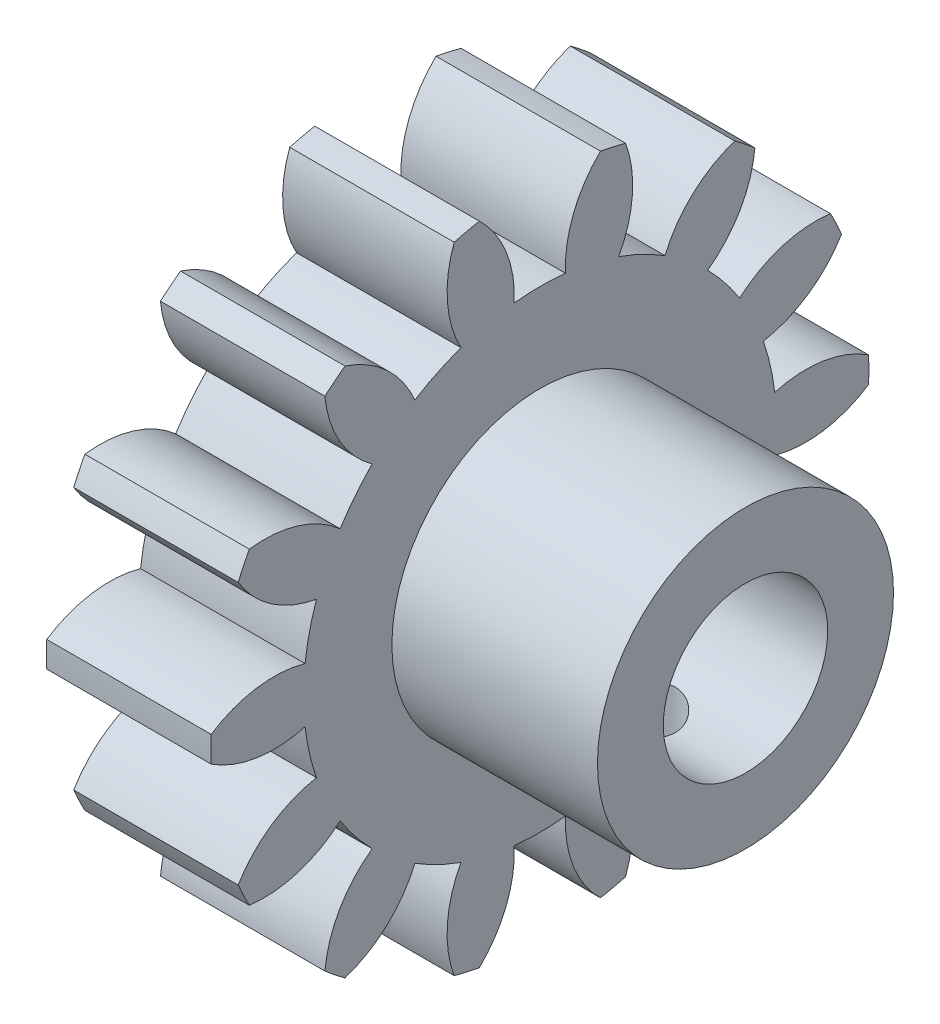
SolidWorks part; units mm, degrees
ref_plane "Plane1" through (0, 0, 0) normal (0, 0, 1) x (1, 0, 0)
ref_plane "Plane2" through (0, 0, 0) normal (0, 1, 0) x (1, 0, 0)
ref_plane "Plane3" through (0, 0, 0) normal (1, 0, 0) x (0, 0, -1)
other "Configuration Table"
sketch "HoldingSke" plane through (0, 0, 0) normal (0, 1, 0) x (1, 0, 0)
  line L0 (0, 0) -> (0.3881, -0.0968)
  line L1 (-15, 0) -> (100, 0) construction
  line L2 (0, 0) -> (-2.1039, 2.3779)
  line L3 (0, 0) -> (-11.863, 4.5341)
  line L4 (0, 0) -> (8.3795, 2.0892)
  line L5 (0, 0) -> (-46.8476, -17.4728)
  line L6 (0, 0) -> (-8.2896, -5.593)
  line L7 (-2.1039, 2.3779) -> (8.6586, 51.2059)
  line L8 (-76.2, 54.61) -> (-74.4, 54.61)
  line L9 (-67.7845, 28.3722) -> (-49.3413, 33.142)
  line L10 (-76.2, 71.12) -> (104.1128, 71.12)
  line L11 (0, 0) -> (-10, 0)
  line L12 (-76.2, 101.6) -> (-76.113, 101.6)
  line L13 (24.9733, 27.94) -> (52.9518, 28.4284)
  line L14 (24.9733, 27.94) -> (24.9743, 27.94)
  line L15 (24.9733, 27.94) -> (100.4006, 29.5858)
  line L16 (-63.627, -2.5) -> (-12.827, -2.5)
  circle A0 centre (0, 0) radius 5
  circle A1 centre (0, 0) radius 14.374
  circle A2 centre (0, 0) radius 37.5
  circle A3 centre (0, 0) radius 5
  dimension "MHD" = 28.748
  dimension "Hub_dia" = 75
  dimension "Bore" = 10
  dimension "MBD" = 10
  dimension "Num_teeth" = 14
  dimension "Pitch" = 0.4
  dimension "Overall_len" = 50
  dimension "Show_teeth" = 14
  dimension "Thickness" = 10
  dimension "OAL" = 50.0001
  dimension "T_dim" = 1.8
  dimension "Ap" = 14.5
  dimension "H" = 19.05
  dimension "Pitch_radius" = 180.3128
  dimension "Width" = 10
  dimension "Backlash" = 0.087
  dimension "Addendum_fac" = 1
  dimension "Dedendum_fac" = 1.25
  dimension "Clearance_fac" = 0.25
  dimension "Dedendum_add" = 0.001
  dimension "Module" = 2.5
sketch "BasProSke" plane through (0, 0, 0) normal (0, 1, 0) x (1, 0, 0)
  line L0 (-10, 0) -> (60, 0) construction
  line L1 (0, 0) -> (0, 20)
  line L2 (0, 0) -> (10, 0)
  line L3 (10, 0) -> (10, 20)
  line L4 (10, 20) -> (0, 20)
  dimension "Thickness" = 10
  dimension "Diameter" = 40
revolve "Base-Revolve" add sketch "BasProSke" angle 360 about L0
sketch "TooCutSke" plane through (0, 0, 0) normal (1, 0, 0) x (0, 0, -1)
  line L1 (0, 0) -> (0, 107) construction
  line L2 (0, 0) -> (-2.1115, 17.3722) construction
  line L3 (0, 0) -> (-7.7466, 33.9401) construction
  line L4 (-2.1115, 17.3722) -> (-3.8733, 16.97) construction
  arc A0 (1.5587, 14.2892) -> (-1.5587, 14.2892) centre (0, 0) ccw
  arc A1 (3.7061, 19.6795) -> (-3.7061, 19.6795) centre (0, 0) ccw
  circle A2 centre (0, 0) radius 17.5 construction
  circle A3 centre (0, 0) radius 16.9426 construction
  arc A4 (-1.5587, 14.2892) -> (-3.7061, 19.6795) centre (-8.5506, 14.6266) ccw
  arc A5 (3.7061, 19.6795) -> (1.5587, 14.2892) centre (8.5506, 14.6266) ccw
  dimension "Root_dia" = 28.748
  dimension "Overcut_dia" = 40.0508
  dimension "Pitch_dia" = 35
  dimension "Base_dia" = 33.8852
  dimension "Flank_rad" = 7
  dimension "Half_ang" = 12.857
  dimension "Half_CT" = 1.8071
extrude "ToothCut" cut sketch "TooCutSke" along normal through all
fillet "Breaks" [suppressed] radius 0.05
fillet "RootFillets" [suppressed] radius 0.626
pattern_circular "TeethCuts" count 14 every 25.714 about axis through (-10, 0, 0) along (1, 0, 0) of "ToothCut", "RootFillets", "Breaks"
sketch "HubNeaOneSke" plane through (0, 0, 0) normal (-1, 0, 0) x (0, 0, 1)
  circle A0 centre (0, 0) radius 14.374
  dimension "Diameter" = 28.748
extrude "HubNearOne" [suppressed] add sketch "HubNeaOneSke" along normal blind 40.0001
sketch "HubNeaBotSke" plane through (0, 0, 0) normal (-1, 0, 0) x (0, 0, 1)
  circle A0 centre (0, 0) radius 14.374
  dimension "Diameter" = 28.748
extrude "HubNearBoth" [suppressed] add sketch "HubNeaBotSke" along normal blind 20
ref_plane "FarPln" through (10, 0, 0) normal (1, 0, 0) x (0, 0, -1)
sketch "HubFarSke" plane through (10, 0, 0) normal (1, 0, 0) x (0, 0, -1)
  circle A0 centre (0, 0) radius 14.374
  dimension "Diameter" = 28.748
extrude "HubFar" [suppressed] add sketch "HubFarSke" along normal blind 20
sketch "BorSke" plane through (0, 0, 0) normal (1, 0, 0) x (0, 0, -1)
  circle A0 centre (0, 0) radius 5
  dimension "Diameter" = 10
extrude "Bore" cut sketch "BorSke" along normal mid plane 100.0001
sketch "KeySke" plane through (0, 0, 0) normal (1, 0, 0) x (0, 0, -1)
  line L0 (-2, 0) -> (-2, 6.8)
  line L1 (-2, 6.8) -> (2, 6.8)
  line L2 (2, 6.8) -> (2, 0)
  line L3 (0, 0) -> (0, 34) construction
  line L4 (-2, 0) -> (2, 0)
  dimension "Offset" = 6.8
  dimension "Width" = 4
extrude "Keyway" [suppressed] cut sketch "KeySke" along normal mid plane 100.0001
pattern_circular "Keyway2" [suppressed] count 2 every 90 about axis through (-10, 0, 0) along (1, 0, 0)
sketch "Esquisse1" plane through (10, 0, 0) normal (1, 0, 0) x (0, 0, -1)
  circle A0 centre (0, 0) radius 5
  circle A1 centre (0, 0) radius 9
extrude "Boss.-Extru.1" add sketch "Esquisse1" along normal blind 12.5
sketch "Esquisse2" plane through (0, 0, 0) normal (0, 1, 0) x (1, 0, 0)
  line L0 (22.5, -9) -> (22.5, 9) construction
  circle A0 centre (16.25, 0) radius 1.9808
  dimension "D1" = 6.25
extrude "Enlèv. mat.-Extru.1" cut sketch "Esquisse2" against normal blind 12.5
equation "' \"Module@HoldingSke\" = 6.35"
equation "' \"Num_teeth@HoldingSke\" = 12"
equation "' \"Ap@HoldingSke\" =  20"
equation "' \"Ap@HoldingSke\" = 20"
equation "' \"Width@HoldingSke\" = 0.5 * 25.4"
equation "' \"Hub_dia@HoldingSke\"= 1 * 25.4"
equation "' \"Hub_dia@HoldingSke\" = 1 * 25.4"
equation "' \"Overall_len@HoldingSke\" = 1.0 * 25.4"
equation "' \"Bore@HoldingSke\" = 0.75 * 25.4"
equation "' \"T_dim@HoldingSke\" = 0.1 * 25.4"
equation "' \"Width@KeySke\" = 0.25 * 25.4"
equation "' \"Show_teeth@HoldingSke\" = 13"
equation "' \"Backlash@HoldingSke\" = 0.009 * 25.4"
equation "' \"Addendum_fac@HoldingSke\" = 1.0"
equation "' \"Dedendum_fac@HoldingSke\" = 1.25"
equation "' \"Dedendum_add@HoldingSke\" = 0.00005 * 25.4"
equation "' \"Clearance_fac@HoldingSke\" = 0.25"
equation "\"Pitch@HoldingSke\" = 1 / \"Module@HoldingSke\""
equation "\"Overcut_dia@TooCutSke\" = (\"Num_teeth@HoldingSke\" + 2 * \"Addendum_fac@HoldingSke\") / \"Pitch@HoldingSke\" + 0.002 * 25.4"
equation "\"Pitch_dia@TooCutSke\" = \"Num_teeth@HoldingSke\" / \"Pitch@HoldingSke\""
equation "\"Base_dia@TooCutSke\" = \"Num_teeth@HoldingSke\" / \"Pitch@HoldingSke\" * cos((\"Ap@HoldingSke\"  * 3.14159265 / 180))"
equation "\"Root_dia@TooCutSke\" = (\"Num_teeth@HoldingSke\" + 2) / \"Pitch@HoldingSke\" - 2 * (\"Addendum_fac@HoldingSke\" + \"Dedendum_fac@HoldingSke\") / \"Pitch@HoldingSke\" - \"Dedendum_add@HoldingSke\" * 2"
equation "\"Half_ang@TooCutSke\" = 180 / \"Num_teeth@HoldingSke\""
equation "\"Half_CT@TooCutSke\" = \"Num_teeth@HoldingSke\" / \"Pitch@HoldingSke\" * sin((3.14159265 / 2 / \"Num_teeth@HoldingSke\")) / 2 - 7 * \"Backlash@HoldingSke\" / 4"
equation "\"Flank_rad@TooCutSke\" = \"Num_teeth@HoldingSke\" / \"Pitch@HoldingSke\" / 5"
equation "\"Radius@RootFillets\" = \"Clearance_fac@HoldingSke\" / \"Pitch@HoldingSke\" + \"Dedendum_add@HoldingSke\""
equation "\"Break_rad@Breaks\" = 0.02 / \"Pitch@HoldingSke\""
equation "\"Thickness@HoldingSke\" = \"Width@HoldingSke\""
equation "\"OAL@HoldingSke\" = \"Thickness@HoldingSke\""
equation "\"MHD@HoldingSke\" = (\"Num_teeth@HoldingSke\" + 2) / \"Pitch@HoldingSke\" - 2 * (\"Addendum_fac@HoldingSke\" + \"Dedendum_fac@HoldingSke\")  / \"Pitch@HoldingSke\" - \"Dedendum_add@HoldingSke\" * 2"
equation "\"MBD@HoldingSke\" = (\"Num_teeth@HoldingSke\" + 2) / \"Pitch@HoldingSke\" - 2 * (\"Addendum_fac@HoldingSke\" + \"Dedendum_fac@HoldingSke\")  / \"Pitch@HoldingSke\" - \"Dedendum_add@HoldingSke\" * 2 - 0.002 * 25.4"
equation "\"MHD@HoldingSke\" = ((sgn( \"MHD@HoldingSke\" - \"Hub_dia@HoldingSke\" )-1)*( \"MHD@HoldingSke\" - \"Hub_dia@HoldingSke\" ))/-2+ \"Hub_dia@HoldingSke\""
equation "\"MBD@HoldingSke\" = ((sgn( \"MBD@HoldingSke\" - \"Bore@HoldingSke\" )-1)*( \"MBD@HoldingSke\" - \"Bore@HoldingSke\" ))/-2+ \"Bore@HoldingSke\""
equation "\"OAL@HoldingSke\" = ((sgn( \"OAL@HoldingSke\" - \"Overall_len@HoldingSke\" )+1)*( \"OAL@HoldingSke\" - \"Overall_len@HoldingSke\" ))/2 + \"Overall_len@HoldingSke\" + 0.000002 * 25.4"
equation "\"Num_teeth@TeethCuts\" = int( \"Show_teeth@HoldingSke\" ) + 1"
equation "\"Num_teeth@TeethCuts\" = ((sgn( \"Num_teeth@TeethCuts\" - \"Num_teeth@HoldingSke\" )-1)*( \"Num_teeth@TeethCuts\" - \"Num_teeth@HoldingSke\" ))/-2+ \"Num_teeth@HoldingSke\""
equation "\"Num_teeth@TeethCuts\" = ((sgn( \"Num_teeth@TeethCuts\" - 2.0)+1)*( \"Num_teeth@TeethCuts\" - 2.0))/2 +2.0"
equation "\"Angle@TeethCuts\" = 360.0 / \"Num_teeth@HoldingSke\""
equation "\"Diameter@BasProSke\" = (\"Num_teeth@HoldingSke\" + 2 * \"Addendum_fac@HoldingSke\") / \"Pitch@HoldingSke\""
equation "\"Thickness@BasProSke\"  = \"Thickness@HoldingSke\""
equation "' \"Fillet_rad@BasProSke\" =  \"Thickness@HoldingSke\" * 0.05"
equation "' \"Fillet_rad@BasProSke\" = \"Thickness@HoldingSke\" * 0.05"
equation "\"MHD@HoldingSke\" = ((sgn( \"MHD@HoldingSke\" - \"Root_dia@TooCutSke\" )-1)*( \"MHD@HoldingSke\" - \"Root_dia@TooCutSke\" ))/-2+ \"Root_dia@TooCutSke\""
equation "\"Diameter@HubNeaOneSke\" = \"MHD@HoldingSke\""
equation "\"Length@HubNearOne\" = \"OAL@HoldingSke\" - \"Thickness@BasProSke\""
equation "\"Diameter@HubNeaBotSke\" = \"MHD@HoldingSke\""
equation "\"Length@HubNearBoth\" = ( \"OAL@HoldingSke\" - \"Thickness@BasProSke\" ) / 2.0"
equation "\"Thickness@FarPln\" = \"Thickness@BasProSke\""
equation "\"Diameter@HubFarSke\" = \"MHD@HoldingSke\""
equation "\"Length@HubFar\" = ( \"OAL@HoldingSke\" - \"Thickness@BasProSke\" ) / 2.0"
equation "\"Diameter@BorSke\" = \"MBD@HoldingSke\""
equation "\"D1@Bore\" = \"OAL@HoldingSke\" * 2.0"
equation "\"D1@Keyway\" = \"OAL@HoldingSke\" * 2.0"
equation "\"Offset@KeySke\" = \"T_dim@HoldingSke\" + \"MBD@HoldingSke\" / 2.0"
